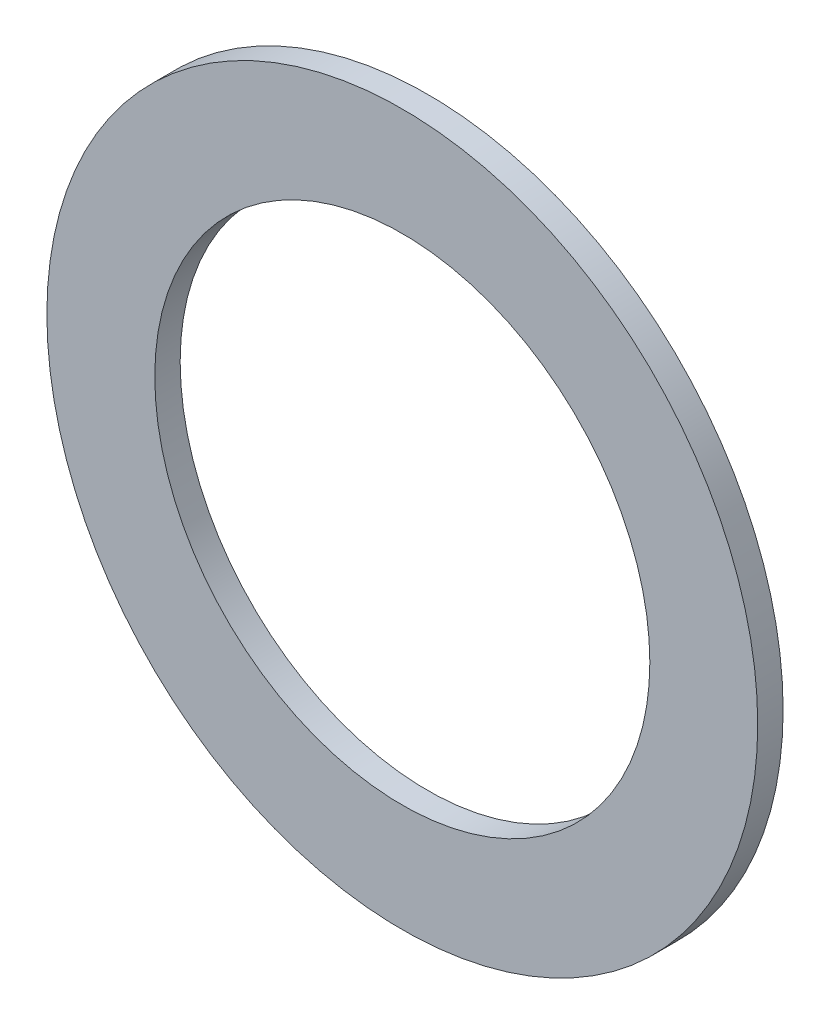
SolidWorks part; units mm, degrees
ref_plane "Face" through (0, 0, 0) normal (0, 0, 1) x (1, 0, 0)
ref_plane "Dessus" through (0, 0, 0) normal (0, 1, 0) x (1, 0, 0)
ref_plane "Droite" through (0, 0, 0) normal (1, 0, 0) x (0, 0, -1)
sketch "Esquisse1" plane through (0, 0, 0) normal (0, 0, 1) x (1, 0, 0)
  circle A0 centre (0, 0) radius 14
  circle A2 centre (0, 0) radius 9.75
  dimension "D1" = 19.5
  dimension "D2" = 28
extrude "Extrusion1" add sketch "Esquisse1" along normal blind 1
